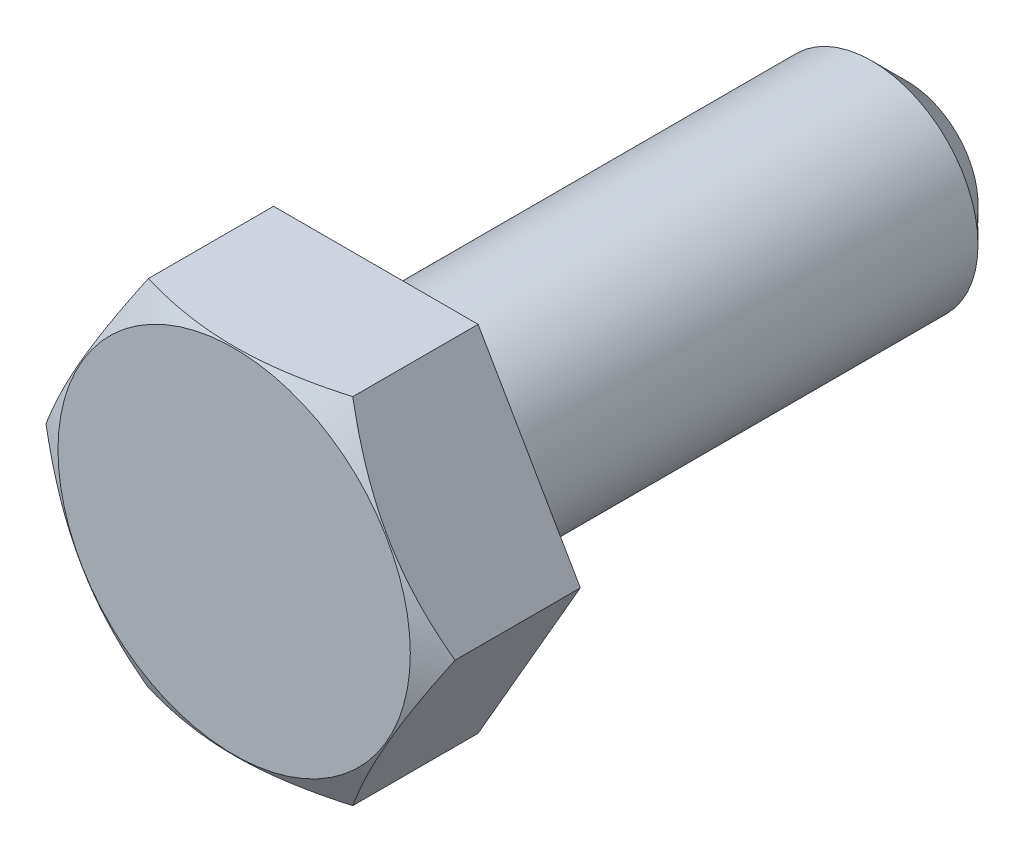
SolidWorks part; units mm, degrees
material "1.0117 (S235J2G4)"
ref_plane "Спереди" through (0, 0, 0) normal (0, 0, 1) x (1, 0, 0)
ref_plane "Сверху" through (0, 0, 0) normal (0, 1, 0) x (1, 0, 0)
ref_plane "Справа" through (0, 0, 0) normal (1, 0, 0) x (0, 0, -1)
sketch "Эскиз1" plane through (0, 0, 0) normal (0, 0, 1) x (1, 0, 0)
  line L1 (5.7735, 0) -> (2.8868, 5)
  line L2 (2.8868, 5) -> (-2.8868, 5)
  line L3 (-2.8868, 5) -> (-5.7735, 0)
  line L4 (-5.7735, 0) -> (-2.8868, -5)
  line L5 (-2.8868, -5) -> (2.8868, -5)
  line L6 (2.8868, -5) -> (5.7735, 0)
  circle A0 centre (0, 0) radius 5 construction
  dimension "D1" = 10
extrude "Бобышка-Вытянуть1" add sketch "Эскиз1" along normal blind 4
sketch "Эскиз2" plane through (0, 0, 0) normal (0, 0, -1) x (-1, 0, 0)
  circle A0 centre (0, 0) radius 3
  dimension "D1" = 6
extrude "Бобышка-Вытянуть2" add sketch "Эскиз2" along normal blind 15
chamfer "Фаска1" distance 1 angle 45 1 edges at (-3, 0, -15)
sketch "Эскиз3" plane through (0, 0, 0) normal (0, 1, 0) x (1, 0, 0)
  line L0 (-10.7735, -0.6514) -> (-4.9735, -4)
  line L1 (0, -4) -> (0, 0) construction
  line L2 (-4.9735, -4) -> (-10.7735, -4)
  line L3 (-10.7735, -4) -> (-10.7735, -0.6514)
  line L5 (2.8868, -4) -> (-2.8868, -4) construction
  line L6 (-5.7735, -4) -> (-5.7735, 0) construction
  line L7 (-2.8868, -4) -> (-5.7735, -4) construction
  dimension "D1" = 0.8
  dimension "D4" = 5
  dimension "D5" = 30
revolve "Вырез-Повернуть1" cut sketch "Эскиз3" angle 360 about L1
